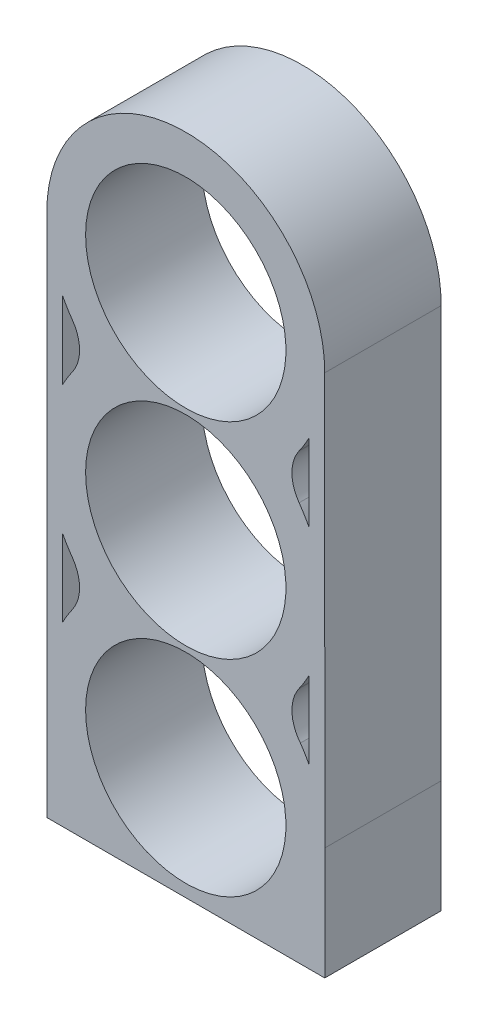
SolidWorks part; units mm, degrees
ref_plane "Front Plane" through (0, 0, 0) normal (0, 0, 1) x (1, 0, 0)
ref_plane "Top Plane" through (0, 0, 0) normal (0, 1, 0) x (1, 0, 0)
ref_plane "Right Plane" through (0, 0, 0) normal (1, 0, 0) x (0, 0, -1)
sketch "Sketch1" plane through (0, 0, 0) normal (0, 0, 1) x (1, 0, 0)
  line L0 (-45.466, 134.62) -> (-45.466, 0)
  line L1 (-40.386, 113.7363) -> (-40.386, 88.1937)
  line L2 (45.466, 134.62) -> (45.4728, 0)
  line L3 (40.387, 113.7383) -> (40.3883, 88.1892)
  line L4 (-40.386, 134.62) -> (-40.386, 0) construction
  line L5 (-40.386, 46.4263) -> (-40.386, 20.8837)
  line L6 (40.3904, 46.4349) -> (40.3917, 20.9254)
  line L7 (40.386, 134.6197) -> (40.3928, -0.0003) construction
  line L9 (-45.466, 0) -> (45.4728, 0)
  line L10 (-45.466, 0) -> (-45.466, -36.83)
  line L11 (-45.466, -36.83) -> (45.4728, -36.83)
  line L12 (45.4728, 0) -> (45.4728, -36.83)
  circle A0 centre (0, 0) radius 32.766
  circle A1 centre (0, 67.31) radius 32.766
  circle A2 centre (0, 134.62) radius 32.766
  arc A3 (37.0825, 108.3133) -> (40.387, 113.7383) centre (0, 134.62) ccw
  arc A4 (-37.0825, 93.6167) -> (-40.386, 88.1937) centre (0, 67.31) ccw
  arc A5 (-37.0825, 26.3067) -> (-40.386, 20.8837) centre (0, 0) ccw
  circle A6 centre (0, 67.31) radius 45.466 construction
  circle A7 centre (0, 134.62) radius 45.466 construction
  circle A8 centre (0, 0) radius 45.466 construction
  arc A9 (37.0825, 41.0033) -> (40.3904, 46.4349) centre (0, 67.31) ccw
  arc A10 (-37.0825, 26.3067) -> (-37.0825, 41.0033) centre (-47.4407, 33.655) ccw
  arc A11 (37.4992, 25.7522) -> (37.0825, 41.0033) centre (47.4407, 33.655) cw
  arc A12 (37.0825, 93.6167) -> (37.0825, 108.3133) centre (47.4407, 100.965) cw
  arc A13 (-37.0825, 93.6167) -> (-37.0825, 108.3133) centre (-47.4407, 100.965) ccw
  arc A14 (-40.386, 113.7363) -> (-37.0825, 108.3133) centre (0, 134.62) ccw
  arc A15 (-40.386, 46.4263) -> (-37.0825, 41.0033) centre (0, 67.31) ccw
  arc A17 (40.3883, 88.1892) -> (37.0825, 93.6167) centre (0, 67.31) ccw
  arc A18 (40.3917, 20.9254) -> (37.4992, 25.7522) centre (0, 0) ccw
  arc A19 (45.466, 134.62) -> (-45.466, 134.62) centre (0, 134.62) ccw
  point P21 (30.5696, 33.655)
  dimension "D1" = 65.532
  dimension "D2" = 65.532
  dimension "D3" = 65.532
  dimension "D7" = 12.7
  dimension "D4" = 67.31
  dimension "D5" = 67.31
  dimension "D9" = 5.08
  dimension "D10" = 36.83
  dimension "D6" = 12.7
  dimension "D8" = 5.08
extrude "Boss-Extrude1" add sketch "Sketch1" along normal blind 38.1 contours L2 A19 L0 L9 A0 L6 A18 A11 A9 L3 A17 A12 A3 L5 A15 A10 A5 L1 A14 A13 A4 A1 A2 | A0 L9 L10 L11 L12
